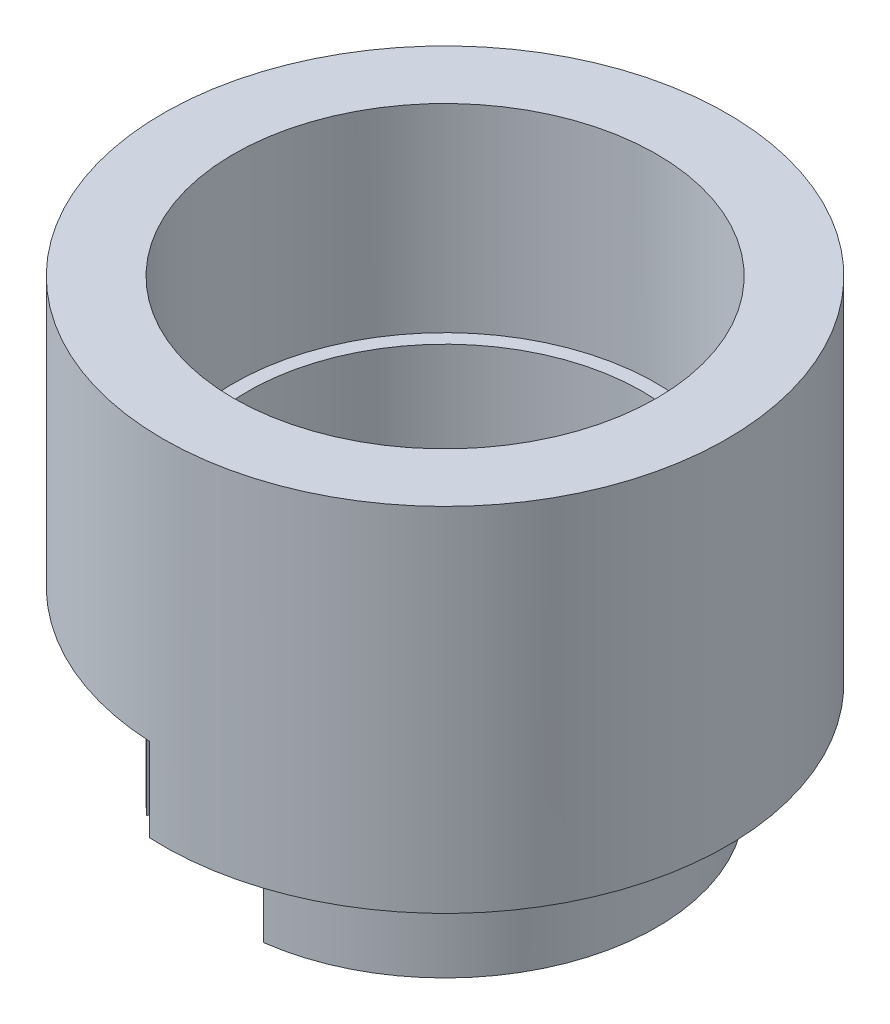
SolidWorks part; units mm, degrees
ref_plane "Plano frontal" through (0, 0, 0) normal (0, 0, 1) x (1, 0, 0)
ref_plane "Plano superior" through (0, 0, 0) normal (0, 1, 0) x (1, 0, 0)
ref_plane "Plano direito" through (0, 0, 0) normal (1, 0, 0) x (0, 0, -1)
sketch "Esboço1" plane through (0, 0, 0) normal (0, 1, 0) x (1, 0, 0)
  circle A0 centre (0, 0) radius 40
  circle A1 centre (0, 0) radius 30
extrude "Ressalto-extrusão1" add sketch "Esboço1" along normal blind 50
ref_plane "Plano1" through (0, 0, 0) normal (0, -1, 0) x (-1, 0, 0)
sketch "Esboço2" plane through (0, 0, 0) normal (0, -1, 0) x (-1, 0, 0)
  line L0 (0, 0) -> (0, -36) construction
  circle A0 centre (0, 0) radius 36 construction
  circle A2 centre (-21.1603, -29.1246) radius 1.5
  circle A3 centre (-34.238, -11.1246) radius 1.5
  circle A4 centre (-34.238, 11.1246) radius 1.5
  circle A7 centre (21.1603, 29.1246) radius 1.5
  circle A8 centre (34.238, 11.1246) radius 1.5
  circle A9 centre (34.238, -11.1246) radius 1.5
  point P25 (0, 0)
extrude "Corte-extrusão1" cut sketch "Esboço2" against normal blind 6
ref_plane "Plano2" through (0, 0, 0) normal (0, -1, 0) x (-1, 0, 0)
sketch "Esboço3" plane through (0, 0, 0) normal (0, -1, 0) x (-1, 0, 0)
  line L0 (16.0924, 28.8103) -> (19.5059, 34.9216)
  line L2 (1.4629, -29.9643) -> (1.9505, -39.9524)
  line L5 (-3.148, 29.8344) -> (-4.1974, 39.7792)
  line L6 (-3.148, 29.8344) -> (-6.3064, 59.7672) construction
  line L7 (30.2939, -13.0873) -> (36.1269, -17.1712)
  line L8 (36.1269, -17.1712) -> (30.2939, -13.0873) construction
  arc A1 (1.4629, -29.9643) -> (-3.148, 29.8344) centre (0, 0) ccw
  arc A2 (1.9505, -39.9524) -> (-4.1974, 39.7792) centre (0, 0) ccw
  arc A3 (30.2939, -13.0873) -> (16.0924, 28.8103) centre (0, 0) ccw
extrude "Corte-extrusão2" cut sketch "Esboço3" against normal blind 11.85 contours L7 A3 L0 A2 L5 A1 L2
ref_plane "Plano3" through (0, 11.85, 0) normal (0, -1, 0) x (-1, 0, 0)
sketch "Esboço4" plane through (0, 11.85, 0) normal (0, -1, 0) x (-1, 0, 0)
  line L0 (-4.0088, -29.7309) -> (-4.7004, -27.6027)
  line L1 (19.9092, -22.4415) -> (19.2303, -20.3518)
  line L2 (-4.0088, -29.7309) -> (-7.1104, -20.1852) construction
  line L3 (16.666, -12.4598) -> (19.9092, -22.4415) construction
  arc A0 (19.9092, -22.4415) -> (-4.0088, -29.7309) centre (0, 0) ccw
  arc A1 (19.2303, -20.3518) -> (-4.7004, -27.6027) centre (0, 0) ccw
extrude "Ressalto-extrusão2" add sketch "Esboço4" along normal blind 26.85 and the other way blind 10
ref_plane "Plano4" through (0, 11.85, 0) normal (0, -1, 0) x (-1, 0, 0)
